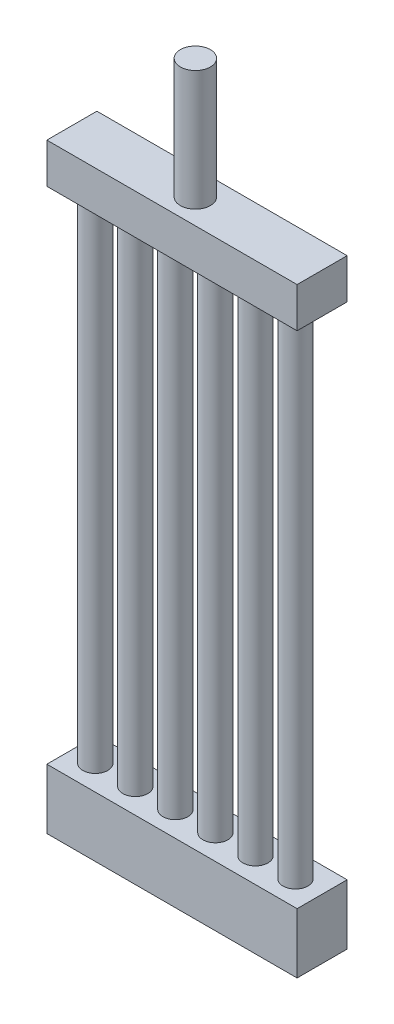
SolidWorks part; units mm, degrees
ref_plane "Front Plane" through (0, 0, 0) normal (0, 0, 1) x (1, 0, 0)
ref_plane "Top Plane" through (0, 0, 0) normal (0, 1, 0) x (1, 0, 0)
ref_plane "Right Plane" through (0, 0, 0) normal (1, 0, 0) x (0, 0, -1)
other "Configuration Table"
sketch "Sketch1" plane through (0, 0, 0) normal (1, 0, 0) x (0, 0, -1)
  line L1 (-34, 190) -> (-39, 190)
  line L2 (-34, 190) -> (-34, 196)
  line L3 (-34, 196) -> (-39, 196)
  line L4 (-39, 190) -> (-39, 196)
  line L5 (-34, 190) -> (-39, 196) construction
  line L6 (-34, 196) -> (-39, 190) construction
  point P0 (-36.5, 193)
extrude "crosshead" add sketch "Sketch1" along normal blind 25 from offset 54 separate body
sketch "Sketch2" plane through (0, 0, 0) normal (0, 1, 0) x (1, 0, 0)
  circle A0 centre (56.34, -36.5) radius 1.25
extrude "sma_spring1" add sketch "Sketch2" along normal blind 50 from offset 196 separate body
sketch "Sketch3" plane through (0, 0, 0) normal (0, 1, 0) x (1, 0, 0)
  circle A0 centre (60.34, -36.5) radius 1.25
extrude "sma_spring2" add sketch "Sketch3" along normal blind 50 from offset 196 separate body
sketch "Sketch4" plane through (0, 0, 0) normal (0, 1, 0) x (1, 0, 0)
  circle A0 centre (64.34, -36.5) radius 1.25
extrude "sma_spring3" add sketch "Sketch4" along normal blind 50 from offset 196 separate body
sketch "Sketch5" plane through (0, 0, 0) normal (0, 1, 0) x (1, 0, 0)
  circle A0 centre (68.34, -36.5) radius 1.25
extrude "sma_spring4" add sketch "Sketch5" along normal blind 50 from offset 196 separate body
sketch "Sketch6" plane through (0, 0, 0) normal (0, 1, 0) x (1, 0, 0)
  circle A0 centre (72.34, -36.5) radius 1.25
extrude "sma_spring5" add sketch "Sketch6" along normal blind 50 from offset 196 separate body
sketch "Sketch7" plane through (0, 0, 0) normal (0, 1, 0) x (1, 0, 0)
  circle A0 centre (76.34, -36.5) radius 1.25
extrude "sma_spring6" add sketch "Sketch7" along normal blind 50 from offset 196 separate body
sketch "Sketch8" plane through (0, 0, 0) normal (1, 0, 0) x (0, 0, -1)
  line L1 (-34, 246) -> (-39, 246)
  line L2 (-34, 246) -> (-34, 250)
  line L3 (-34, 250) -> (-39, 250)
  line L4 (-39, 246) -> (-39, 250)
  line L5 (-34, 246) -> (-39, 250) construction
  line L6 (-34, 250) -> (-39, 246) construction
  point P0 (-36.5, 248)
extrude "anchor_plate" add sketch "Sketch8" along normal blind 25 from offset 54 separate body
sketch "Sketch9" plane through (0, 0, 0) normal (0, 1, 0) x (1, 0, 0)
  circle A0 centre (66.34, -36.5) radius 1.5
extrude "hook" add sketch "Sketch9" along normal blind 12 from offset 250 separate body
